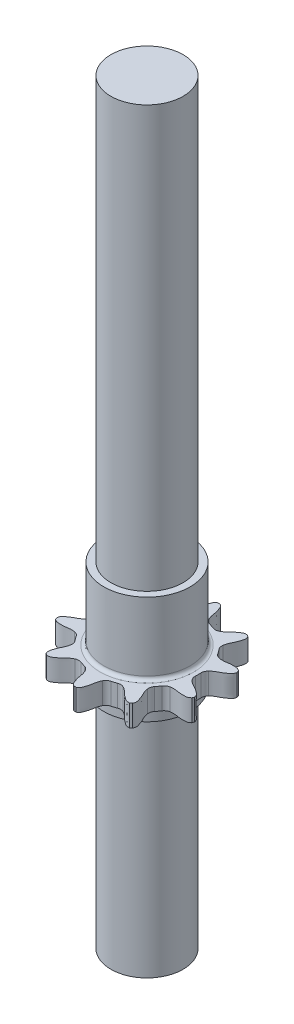
SolidWorks part; units mm, degrees
ref_plane "Front Plane" through (0, 0, 0) normal (0, 0, 1) x (1, 0, 0)
ref_plane "Top Plane" through (0, 0, 0) normal (0, 1, 0) x (1, 0, 0)
ref_plane "Right Plane" through (0, 0, 0) normal (1, 0, 0) x (0, 0, -1)
sketch "Sketch1" plane through (0, 0, 0) normal (0, 1, 0) x (1, 0, 0)
  circle A0 centre (0, 0) radius 5
  circle A1 centre (0, 0) radius 6
  arc A2 (-3.3515, -6.6776) -> (-2.5431, -6.6366) centre (-2.901, -7.5704) cw
  arc A3 (-7.0976, 0.3679) -> (-7.0976, -0.3679) centre (0, 0) ccw
  arc A4 (-5.3151, -5.2509) -> (-5.5259, -4.4695) centre (-6.3034, -5.0983) ccw
  arc A5 (-6.004, -7.997) -> (-5.7502, -8.1814) centre (0, 0) ccw
  arc A6 (-6.6364, -3.4323) -> (-5.9583, -3.8743) centre (-6.7967, -4.4194) cw
  arc A7 (-7.3864, -1.1239) -> (-7.0976, -0.3679) centre (-8.0963, -0.4196) ccw
  arc A8 (-0.1569, -9.9988) -> (0.1569, -9.9988) centre (0, 0) ccw
  arc A9 (-9.5579, -2.9406) -> (-9.4609, -3.239) centre (0, 0) ccw
  arc A10 (-7.3864, 1.1239) -> (-7.0976, 0.3679) centre (-8.0963, 0.4196) cw
  arc A11 (-5.9583, -3.8743) -> (-5.5259, -4.4695) centre (0, 0) ccw
  arc A12 (-2.5431, -6.6366) -> (-1.8434, -6.8639) centre (0, 0) ccw
  arc A13 (1.8434, -6.8639) -> (2.5431, -6.6366) centre (0, 0) ccw
  arc A14 (5.5259, -4.4695) -> (5.9583, -3.8743) centre (0, 0) ccw
  arc A15 (7.0976, -0.3679) -> (7.0976, 0.3679) centre (0, 0) ccw
  arc A16 (5.9583, 3.8743) -> (5.5259, 4.4695) centre (0, 0) ccw
  arc A17 (2.5431, 6.6366) -> (1.8434, 6.8639) centre (0, 0) ccw
  arc A18 (-6.6364, 3.4323) -> (-5.9583, 3.8743) centre (-6.7967, 4.4194) ccw
  arc A19 (-9.4609, 3.239) -> (-9.5579, 2.9406) centre (0, 0) ccw
  arc A20 (-5.3151, 5.2509) -> (-5.5259, 4.4695) centre (-6.3034, 5.0983) cw
  arc A21 (-3.3515, 6.6776) -> (-2.5431, 6.6366) centre (-2.901, 7.5704) ccw
  arc A22 (-5.7502, 8.1814) -> (-6.004, 7.997) centre (0, 0) ccw
  arc A23 (-1.2136, 7.3722) -> (-1.8434, 6.8639) centre (-2.1028, 7.8297) cw
  arc A24 (-1.2136, -7.3722) -> (-1.8434, -6.8639) centre (-2.1028, -7.8297) ccw
  arc A25 (1.2136, -7.3722) -> (1.8434, -6.8639) centre (2.1028, -7.8297) cw
  arc A26 (1.2136, 7.3722) -> (1.8434, 6.8639) centre (2.1028, 7.8297) ccw
  arc A27 (0.1569, 9.9988) -> (-0.1569, 9.9988) centre (0, 0) ccw
  arc A28 (3.3515, 6.6776) -> (2.5431, 6.6366) centre (2.901, 7.5704) cw
  arc A29 (5.3151, 5.2509) -> (5.5259, 4.4695) centre (6.3034, 5.0983) ccw
  arc A30 (6.004, 7.997) -> (5.7502, 8.1814) centre (0, 0) ccw
  arc A31 (6.6364, 3.4323) -> (5.9583, 3.8743) centre (6.7967, 4.4194) cw
  arc A32 (7.3864, 1.1239) -> (7.0976, 0.3679) centre (8.0963, 0.4196) ccw
  arc A33 (9.5579, 2.9406) -> (9.4609, 3.239) centre (0, 0) ccw
  arc A34 (7.3864, -1.1239) -> (7.0976, -0.3679) centre (8.0963, -0.4196) cw
  arc A35 (6.6364, -3.4323) -> (5.9583, -3.8743) centre (6.7967, -4.4194) ccw
  arc A36 (9.4609, -3.239) -> (9.5579, -2.9406) centre (0, 0) ccw
  arc A37 (5.3151, -5.2509) -> (5.5259, -4.4695) centre (6.3034, -5.0983) cw
  arc A38 (3.3515, -6.6776) -> (2.5431, -6.6366) centre (2.901, -7.5704) ccw
  arc A39 (5.7502, -8.1814) -> (6.004, -7.997) centre (0, 0) ccw
  arc A40 (-1.8434, 6.8639) -> (-2.5431, 6.6366) centre (0, 0) ccw
  arc A41 (-5.5259, 4.4695) -> (-5.9583, 3.8743) centre (0, 0) ccw
  spline S0 degree 3 poles (-6.004, -7.997) (-6.006, -7.9918) (-6.0495, -7.8781) (-6.1535, -7.6065) (-6.0097, -7.138) (-5.8221, -6.4844) (-5.4423, -5.889) (-5.3392, -5.4071) (-5.3151, -5.2509) knots -0.004717 -0.004717 -0.004717 -0.004717 0.000118 0.105683 0.243127 0.421867 0.719007 0.859817 0.859817 0.859817 0.859817
  spline S1 degree 3 poles (-5.7502, -8.1814) (-5.7447, -8.1817) (-5.6231, -8.1879) (-5.3327, -8.2029) (-4.9315, -7.9214) (-4.3679, -7.5409) (-3.919, -6.9958) (-3.4925, -6.7488) (-3.3515, -6.6776) knots -0.004717 -0.004717 -0.004717 -0.004717 0.000118 0.105683 0.243127 0.421867 0.719007 0.859817 0.859817 0.859817 0.859817
  spline S2 degree 3 poles (-9.5579, -2.9406) (-9.5564, -2.9352) (-9.5248, -2.8177) (-9.4493, -2.5369) (-9.0576, -2.2423) (-8.5216, -1.8239) (-7.8644, -1.5654) (-7.4977, -1.2361) (-7.3864, -1.1239) knots -0.004717 -0.004717 -0.004717 -0.004717 0.000118 0.105683 0.243127 0.421867 0.719007 0.859817 0.859817 0.859817 0.859817
  spline S3 degree 3 poles (-9.4609, -3.239) (-9.4566, -3.2425) (-9.3619, -3.319) (-9.1358, -3.5017) (-8.6457, -3.5099) (-7.9662, -3.5333) (-7.2826, -3.3562) (-6.7923, -3.407) (-6.6364, -3.4323) knots -0.004717 -0.004717 -0.004717 -0.004717 0.000118 0.105683 0.243127 0.421867 0.719007 0.859817 0.859817 0.859817 0.859817
  spline S4 degree 3 poles (-9.4609, 3.239) (-9.4566, 3.2425) (-9.3619, 3.319) (-9.1358, 3.5017) (-8.6457, 3.5099) (-7.9662, 3.5333) (-7.2826, 3.3562) (-6.7923, 3.407) (-6.6364, 3.4323) knots -0.004717 -0.004717 -0.004717 -0.004717 0.000118 0.105683 0.243127 0.421867 0.719007 0.859817 0.859817 0.859817 0.859817
  spline S5 degree 3 poles (-9.5579, 2.9406) (-9.5564, 2.9352) (-9.5248, 2.8177) (-9.4493, 2.5369) (-9.0576, 2.2423) (-8.5216, 1.8239) (-7.8644, 1.5654) (-7.4977, 1.2361) (-7.3864, 1.1239) knots -0.004717 -0.004717 -0.004717 -0.004717 0.000118 0.105683 0.243127 0.421867 0.719007 0.859817 0.859817 0.859817 0.859817
  spline S6 degree 3 poles (-5.7502, 8.1814) (-5.7447, 8.1817) (-5.6231, 8.1879) (-5.3327, 8.2029) (-4.9315, 7.9214) (-4.3679, 7.5409) (-3.919, 6.9958) (-3.4925, 6.7488) (-3.3515, 6.6776) knots -0.004717 -0.004717 -0.004717 -0.004717 0.000118 0.105683 0.243127 0.421867 0.719007 0.859817 0.859817 0.859817 0.859817
  spline S7 degree 3 poles (-6.004, 7.997) (-6.006, 7.9918) (-6.0495, 7.8781) (-6.1535, 7.6065) (-6.0097, 7.138) (-5.8221, 6.4844) (-5.4423, 5.889) (-5.3392, 5.4071) (-5.3151, 5.2509) knots -0.004717 -0.004717 -0.004717 -0.004717 0.000118 0.105683 0.243127 0.421867 0.719007 0.859817 0.859817 0.859817 0.859817
  spline S8 degree 3 poles (0.1569, -9.9988) (0.1615, -9.9957) (0.2636, -9.9293) (0.5072, -9.7707) (0.6664, -9.3072) (0.8987, -8.6681) (0.9415, -7.9632) (1.1413, -7.5127) (1.2136, -7.3722) knots -0.004717 -0.004717 -0.004717 -0.004717 0.000118 0.105683 0.243127 0.421867 0.719007 0.859817 0.859817 0.859817 0.859817
  spline S9 degree 3 poles (-0.1569, -9.9988) (-0.1615, -9.9957) (-0.2636, -9.9293) (-0.5072, -9.7707) (-0.6664, -9.3072) (-0.8987, -8.6681) (-0.9415, -7.9632) (-1.1413, -7.5127) (-1.2136, -7.3722) knots -0.004717 -0.004717 -0.004717 -0.004717 0.000118 0.105683 0.243127 0.421867 0.719007 0.859817 0.859817 0.859817 0.859817
  spline S10 degree 3 poles (0.1569, 9.9988) (0.1615, 9.9957) (0.2636, 9.9293) (0.5072, 9.7707) (0.6664, 9.3072) (0.8987, 8.6681) (0.9415, 7.9632) (1.1413, 7.5127) (1.2136, 7.3722) knots -0.004717 -0.004717 -0.004717 -0.004717 0.000118 0.105683 0.243127 0.421867 0.719007 0.859817 0.859817 0.859817 0.859817
  spline S11 degree 3 poles (-0.1569, 9.9988) (-0.1615, 9.9957) (-0.2636, 9.9293) (-0.5072, 9.7707) (-0.6664, 9.3072) (-0.8987, 8.6681) (-0.9415, 7.9632) (-1.1413, 7.5127) (-1.2136, 7.3722) knots -0.004717 -0.004717 -0.004717 -0.004717 0.000118 0.105683 0.243127 0.421867 0.719007 0.859817 0.859817 0.859817 0.859817
  spline S12 degree 3 poles (6.004, 7.997) (6.006, 7.9918) (6.0495, 7.8781) (6.1535, 7.6065) (6.0097, 7.138) (5.8221, 6.4844) (5.4423, 5.889) (5.3392, 5.4071) (5.3151, 5.2509) knots -0.004717 -0.004717 -0.004717 -0.004717 0.000118 0.105683 0.243127 0.421867 0.719007 0.859817 0.859817 0.859817 0.859817
  spline S13 degree 3 poles (5.7502, 8.1814) (5.7447, 8.1817) (5.6231, 8.1879) (5.3327, 8.2029) (4.9315, 7.9214) (4.3679, 7.5409) (3.919, 6.9958) (3.4925, 6.7488) (3.3515, 6.6776) knots -0.004717 -0.004717 -0.004717 -0.004717 0.000118 0.105683 0.243127 0.421867 0.719007 0.859817 0.859817 0.859817 0.859817
  spline S14 degree 3 poles (9.5579, 2.9406) (9.5564, 2.9352) (9.5248, 2.8177) (9.4493, 2.5369) (9.0576, 2.2423) (8.5216, 1.8239) (7.8644, 1.5654) (7.4977, 1.2361) (7.3864, 1.1239) knots -0.004717 -0.004717 -0.004717 -0.004717 0.000118 0.105683 0.243127 0.421867 0.719007 0.859817 0.859817 0.859817 0.859817
  spline S15 degree 3 poles (9.4609, 3.239) (9.4566, 3.2425) (9.3619, 3.319) (9.1358, 3.5017) (8.6457, 3.5099) (7.9662, 3.5333) (7.2826, 3.3562) (6.7923, 3.407) (6.6364, 3.4323) knots -0.004717 -0.004717 -0.004717 -0.004717 0.000118 0.105683 0.243127 0.421867 0.719007 0.859817 0.859817 0.859817 0.859817
  spline S16 degree 3 poles (9.4609, -3.239) (9.4566, -3.2425) (9.3619, -3.319) (9.1358, -3.5017) (8.6457, -3.5099) (7.9662, -3.5333) (7.2826, -3.3562) (6.7923, -3.407) (6.6364, -3.4323) knots -0.004717 -0.004717 -0.004717 -0.004717 0.000118 0.105683 0.243127 0.421867 0.719007 0.859817 0.859817 0.859817 0.859817
  spline S17 degree 3 poles (9.5579, -2.9406) (9.5564, -2.9352) (9.5248, -2.8177) (9.4493, -2.5369) (9.0576, -2.2423) (8.5216, -1.8239) (7.8644, -1.5654) (7.4977, -1.2361) (7.3864, -1.1239) knots -0.004717 -0.004717 -0.004717 -0.004717 0.000118 0.105683 0.243127 0.421867 0.719007 0.859817 0.859817 0.859817 0.859817
  spline S18 degree 3 poles (5.7502, -8.1814) (5.7447, -8.1817) (5.6231, -8.1879) (5.3327, -8.2029) (4.9315, -7.9214) (4.3679, -7.5409) (3.919, -6.9958) (3.4925, -6.7488) (3.3515, -6.6776) knots -0.004717 -0.004717 -0.004717 -0.004717 0.000118 0.105683 0.243127 0.421867 0.719007 0.859817 0.859817 0.859817 0.859817
  spline S19 degree 3 poles (6.004, -7.997) (6.006, -7.9918) (6.0495, -7.8781) (6.1535, -7.6065) (6.0097, -7.138) (5.8221, -6.4844) (5.4423, -5.889) (5.3392, -5.4071) (5.3151, -5.2509) knots -0.004717 -0.004717 -0.004717 -0.004717 0.000118 0.105683 0.243127 0.421867 0.719007 0.859817 0.859817 0.859817 0.859817
extrude "Extrude1" add sketch "Sketch1" against normal blind 3
sketch "Sketch2" plane through (0, -3, 0) normal (0, -1, 0) x (1, 0, 0)
  circle A0 centre (0, 0) radius 5
  circle A1 centre (0, 0) radius 6
extrude "Extrude2" add sketch "Sketch2" along normal blind 2 and the other way blind 13
fillet "Fillet1" radius 0.5 2 edges at (0, 0, 6) (0, -3, 6)
ref_plane "Plane1" through (0, -1.5, 0) normal (0, -1, 0) x (-1, 0, 0)
sketch "Sketch3" plane through (0, -1.5, 0) normal (0, -1, 0) x (-1, 0, 0)
  circle A0 centre (0, 0) radius 5.0155
extrude "Boss-Extrude1" add sketch "Sketch3" along normal blind 35 and the other way blind 70
sketch "Sketch4" plane through (0, -3, 0) normal (0, -1, 0) x (-1, 0, 0)
  line L0 (0, 0) -> (-2.1962, -6.7593) construction
  line L1 (-2.1962, -6.7593) -> (-4.536, -13.9603) construction
  line L2 (-2.7525, -8.4712) -> (-6.8426, -7.1422) construction
  arc A0 (-2.5431, -6.6366) -> (-1.8434, -6.8639) centre (0, 0) ccw construction
  circle A1 centre (-2.7525, -8.4712) radius 1.8
  dimension "D2" = 3.6
  dimension "D1" = 1.8
sketch "Sketch5" plane through (0, -3, 0) normal (0, -1, 0) x (1, 0, 0)
  line L0 (0, 0) -> (-2.1962, 6.7593) construction
  line L1 (-2.1962, 6.7593) -> (-4.8279, 14.8587) construction
  line L2 (2.7525, 8.4712) -> (-2.7525, 8.4712) construction
  arc A0 (-1.8434, 6.8639) -> (-2.5431, 6.6366) centre (0, 0) ccw construction
  circle A1 centre (-2.7525, 8.4712) radius 1.8
